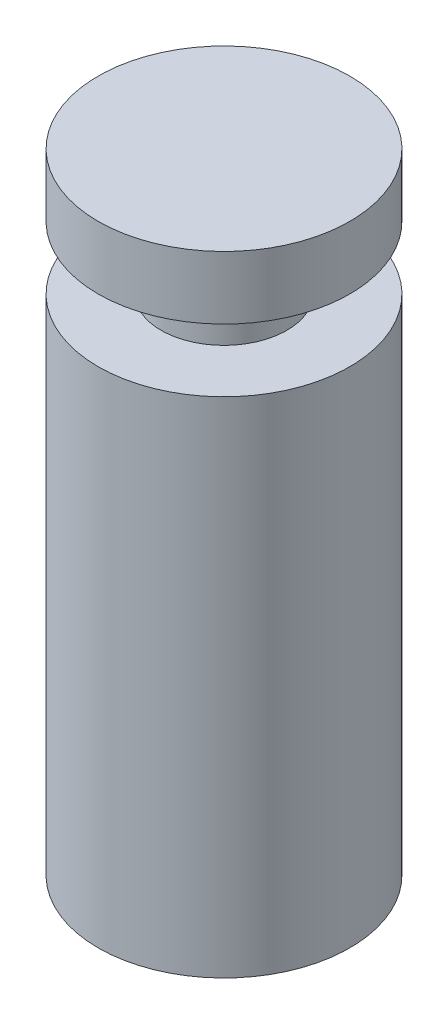
SolidWorks part; units mm, degrees
ref_plane "Alzado" through (0, 0, 0) normal (0, 0, 1) x (1, 0, 0)
ref_plane "Planta" through (0, 0, 0) normal (0, 1, 0) x (1, 0, 0)
ref_plane "Vista lateral" through (0, 0, 0) normal (1, 0, 0) x (0, 0, -1)
sketch "Croquis2" plane through (0, 0, 0) normal (1, 0, 0) x (0, 0, -1)
  line L0 (0, 0) -> (0, 20)
  line L1 (0, 20) -> (4, 20)
  line L2 (4, 18) -> (2, 18)
  line L3 (2, 18) -> (2, 16)
  line L4 (2, 16) -> (4, 16)
  line L5 (4, 16) -> (4, 0)
  line L6 (0, 0) -> (4, 0)
  line L7 (4, 20) -> (4, 18)
  dimension "D1" = 20
  dimension "D2" = 4
  dimension "D3" = 2
  dimension "D4" = 2
  dimension "D5" = 2
revolve "Revolución1" add sketch "Croquis2" angle 360 about L0
